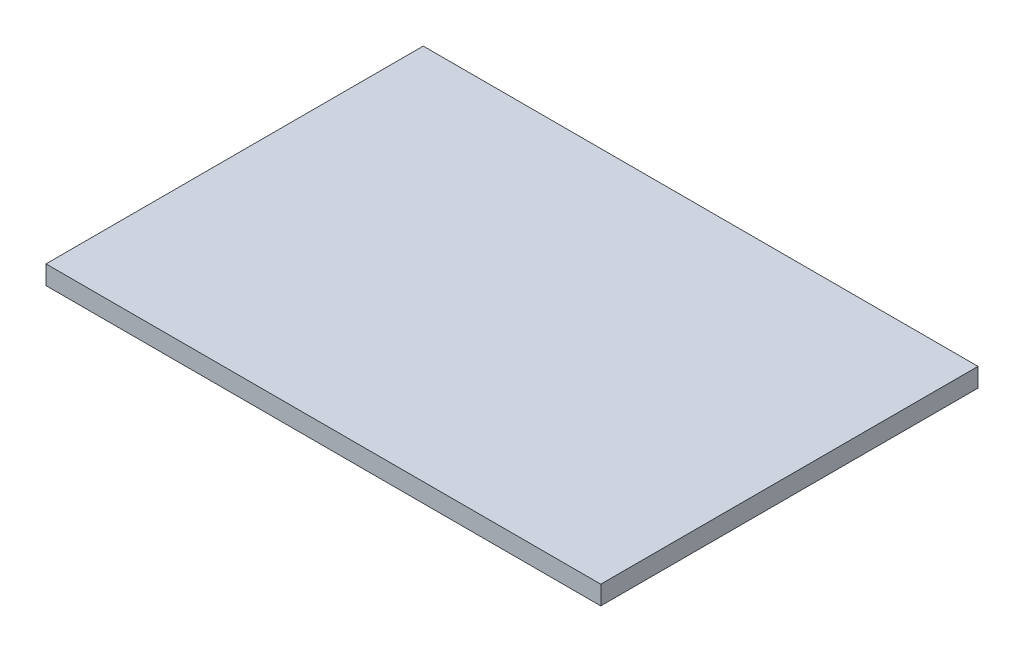
SolidWorks part; units mm, degrees
ref_plane "Front Plane" through (0, 0, 0) normal (0, 0, 1) x (1, 0, 0)
ref_plane "Top Plane" through (0, 0, 0) normal (0, 1, 0) x (1, 0, 0)
ref_plane "Right Plane" through (0, 0, 0) normal (1, 0, 0) x (0, 0, -1)
sketch "Sketch1" plane through (0, 0, 0) normal (0, 1, 0) x (1, 0, 0)
  line L1 (-25, 17) -> (25, 17)
  line L2 (-25, 17) -> (-25, -17)
  line L3 (-25, -17) -> (25, -17)
  line L4 (25, 17) -> (25, -17)
  line L5 (-25, 17) -> (25, -17) construction
  line L6 (-25, -17) -> (25, 17) construction
  point P0 (0, 0)
  dimension "D1" = 34
  dimension "D2" = 50
extrude "Boss-Extrude1" add sketch "Sketch1" along normal blind 1.7
sketch "Sketch2" plane through (0, 0, 0) normal (0, -1, 0) x (1, 0, 0)
  line L1 (21.6, -14.5) -> (7.9, -14.5)
  line L2 (21.6, -14.5) -> (21.6, -0.5)
  line L3 (21.6, -0.5) -> (7.9, -0.5)
  line L4 (7.9, -14.5) -> (7.9, -0.5)
  line L5 (25, 17) -> (25, -17) construction
  line L6 (25, -17) -> (-25, -17) construction
  dimension "D1" = 13.7
  dimension "D2" = 14
  dimension "D3" = 3.4
  dimension "D4" = 2.5
extrude "Boss-Extrude2" add sketch "Sketch2" along normal blind 2.2 separate body
